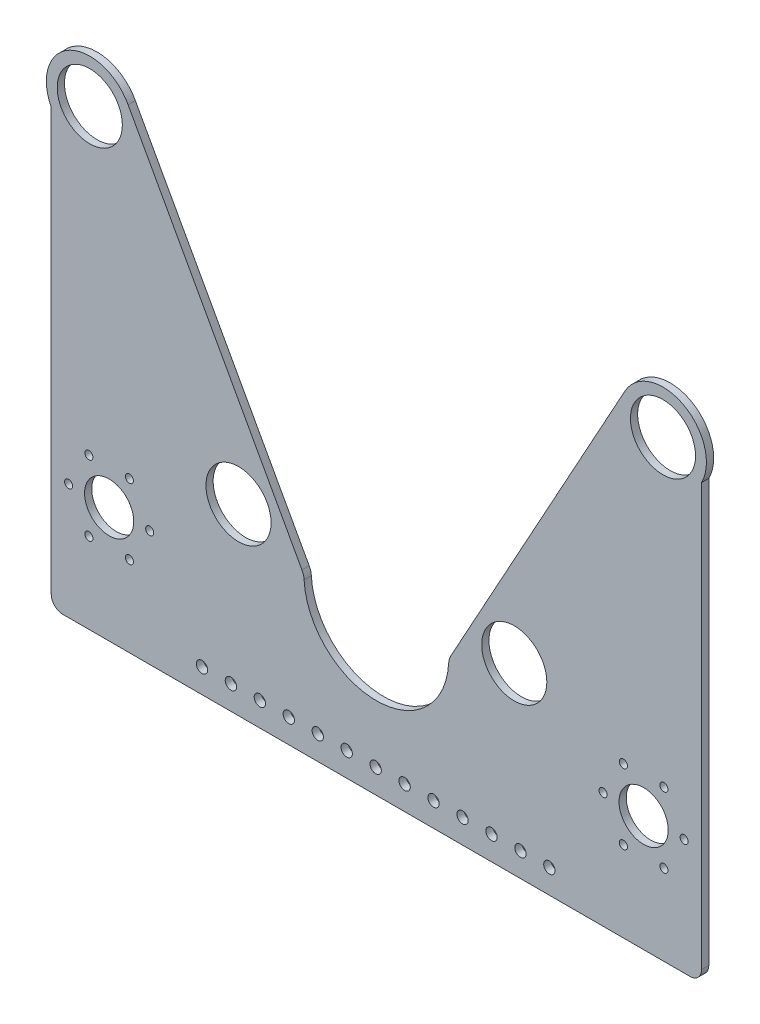
SolidWorks part; units mm, degrees
ref_plane "Front Plane" through (0, 0, 0) normal (0, 0, 1) x (1, 0, 0)
ref_plane "Top Plane" through (0, 0, 0) normal (0, 1, 0) x (1, 0, 0)
ref_plane "Right Plane" through (0, 0, 0) normal (1, 0, 0) x (0, 0, -1)
sketch "Sketch2" plane through (0, 0, 0) normal (0, 0, 1) x (1, 0, 0)
  line L0 (-106.68, -1076.9295) -> (-106.68, 48923.0705) construction
  line L1 (142.6324, 122.4629) -> (142.6324, -29.9371)
  line L2 (106.68, -1098.4025) -> (106.68, 48901.5975) construction
  line L3 (31.75, 0) -> (108.9183, 140.209)
  line L4 (0, -1082.0685) -> (0, 48917.9315) construction
  line L5 (-106.68, -44.45) -> (106.68, -44.45) construction
  line L8 (106.68, -55.9582) -> (106.68, -31.75)
  line L9 (-31.75, 0) -> (-108.9183, 140.209)
  line L10 (31.75, 0) -> (108.9183, 140.209)
  line L22 (-142.6324, -56.7419) -> (-142.6324, -62.6205)
  line L33 (-106.5644, -31.75) -> (0, -31.75) construction
  line L34 (-142.6324, 122.4629) -> (-142.6324, -29.9371)
  line L36 (-261.1394, 46.2048) -> (-243.4617, 46.2048) construction
  line L37 (-243.4617, 46.2048) -> (-243.4617, 28.5272) construction
  line L41 (-238.3305, 62.766) -> (-266.2705, 62.766) construction
  line L42 (-233.2505, 57.686) -> (-233.2505, 17.046) construction
  line L43 (-261.1394, 46.2048) -> (-261.1394, 28.5272) construction
  line L44 (-261.1394, 28.5272) -> (-243.4617, 28.5272) construction
  line L45 (-238.3305, 11.966) -> (-266.2705, 11.966) construction
  line L46 (-271.3505, 57.686) -> (-271.3505, 17.046) construction
  line L47 (-233.2505, 62.766) -> (-271.3505, 11.966) construction
  line L48 (-125.73, 3.175) -> (-125.73, -22.225) construction
  line L49 (-1101.9372, -9.525) -> (48898.0628, -9.525) construction
  line L50 (-233.2505, 11.966) -> (-271.3505, 62.766) construction
  line L51 (-239.6005, 56.416) -> (-239.6005, 18.316) construction
  line L52 (-265.0005, 56.416) -> (-239.6005, 56.416) construction
  line L53 (-125.73, 3.175) -> (-106.68, 3.175) construction
  line L54 (-142.6324, -56.7419) -> (142.6324, -56.7419) construction
  line L55 (-142.6324, -29.9371) -> (-142.6324, -56.7419)
  line L56 (142.6324, -29.9371) -> (142.6324, -56.7419)
  line L57 (-137.5524, -67.7005) -> (137.5524, -67.7005)
  line L58 (142.6324, -62.6205) -> (142.6324, -56.7419)
  arc A0 (-31.75, 0) -> (31.75, 0) centre (0, 0) ccw
  arc A1 (-108.9183, 140.209) -> (-142.6324, 122.4629) centre (-125.7268, 131.2438) ccw
  circle A2 centre (-60.4845, 12.7) radius 14.2875
  arc A3 (31.75, 0) -> (0, 31.75) centre (0, 0) ccw construction
  arc A4 (0, 31.75) -> (-31.75, 0) centre (0, 0) ccw construction
  arc A5 (137.5524, -67.7005) -> (142.6324, -62.6205) centre (137.5524, -62.6205) ccw
  arc A6 (-142.6324, -62.6205) -> (-137.5524, -67.7005) centre (-137.5524, -62.6205) ccw
  circle A7 centre (-125.7268, 131.2438) radius 14.2875
  circle A9 centre (-60.4845, 12.7) radius 19.05 construction
  circle A10 centre (60.4845, 12.7) radius 19.05 construction
  arc A11 (108.9183, 140.209) -> (142.6324, 122.4629) centre (125.7268, 131.2438) cw
  circle A12 centre (125.7268, 131.2438) radius 14.2875
  arc A40 (-142.6324, 122.4629) -> (-108.9183, 140.209) centre (-125.7268, 131.2438) ccw construction
  arc A41 (142.6324, 122.4629) -> (108.9183, 140.209) centre (125.7268, 131.2438) cw construction
  circle A42 centre (60.4845, 12.7) radius 14.2875
  circle A44 centre (-76.5175, -57.15) radius 2.4892
  circle A45 centre (-63.8175, -57.15) radius 2.4892
  circle A46 centre (-51.1175, -57.15) radius 2.4892
  circle A47 centre (-38.4175, -57.15) radius 2.4892
  circle A48 centre (-25.7175, -57.15) radius 2.4892
  circle A49 centre (-13.0175, -57.15) radius 2.4892
  circle A50 centre (-0.3175, -57.15) radius 2.4892
  circle A51 centre (12.3825, -57.15) radius 2.4892
  circle A52 centre (25.0825, -57.15) radius 2.4892
  circle A53 centre (37.7825, -57.15) radius 2.4892
  circle A54 centre (50.4825, -57.15) radius 2.4892
  circle A55 centre (63.1825, -57.15) radius 2.4892
  circle A56 centre (75.8825, -57.15) radius 2.4892
  arc A100 (-260.1552, 27.7564) -> (-262.1235, 29.2979) centre (-261.1394, 28.5272) ccw construction
  arc A101 (-262.1235, 29.2979) -> (-260.1552, 27.7564) centre (-261.1394, 28.5272) ccw construction
  arc A102 (-244.4458, 29.2979) -> (-242.4776, 27.7564) centre (-243.4617, 28.5272) ccw construction
  arc A103 (-242.4776, 27.7564) -> (-244.4458, 29.2979) centre (-243.4617, 28.5272) ccw construction
  arc A104 (-242.4776, 45.4341) -> (-244.4458, 46.9756) centre (-243.4617, 46.2048) ccw construction
  arc A105 (-244.4458, 46.9756) -> (-242.4776, 45.4341) centre (-243.4617, 46.2048) ccw construction
  arc A106 (-262.1235, 46.9756) -> (-260.1552, 45.4341) centre (-261.1394, 46.2048) ccw construction
  arc A107 (-260.1552, 45.4341) -> (-262.1235, 46.9756) centre (-261.1394, 46.2048) ccw construction
  circle A108 centre (-252.3005, 37.366) radius 7.3172 construction
  circle A109 centre (-265.0005, 56.416) radius 3.175 construction
  circle A110 centre (-239.6005, 56.416) radius 3.175 construction
  circle A111 centre (-239.6005, 18.316) radius 3.175 construction
  circle A112 centre (-265.0005, 18.316) radius 3.175 construction
  arc A113 (-266.2705, 11.966) -> (-271.3505, 17.046) centre (-266.2705, 17.046) cw construction
  arc A114 (-233.2505, 17.046) -> (-238.3305, 11.966) centre (-238.3305, 17.046) cw construction
  arc A115 (-238.3305, 62.766) -> (-233.2505, 57.686) centre (-238.3305, 57.686) cw construction
  arc A116 (-266.2705, 62.766) -> (-271.3505, 57.686) centre (-266.2705, 57.686) ccw construction
  circle A128 centre (-117.2324, -16.9005) radius 10.795
  circle A129 centre (117.2324, -16.9005) radius 10.795
  circle A132 centre (-135.0124, -16.9005) radius 1.778
  circle A133 centre (-126.1224, -1.5026) radius 1.778
  circle A134 centre (-108.3424, -1.5026) radius 1.778
  circle A135 centre (-99.4524, -16.9005) radius 1.778
  circle A136 centre (-108.3424, -32.2984) radius 1.778
  circle A137 centre (-126.1224, -32.2984) radius 1.778
  circle A138 centre (99.4524, -16.9005) radius 1.778
  circle A139 centre (108.3424, -1.5026) radius 1.778
  circle A140 centre (126.1224, -1.5026) radius 1.778
  circle A141 centre (135.0124, -16.9005) radius 1.778
  circle A142 centre (126.1224, -32.2984) radius 1.778
  circle A143 centre (108.3424, -32.2984) radius 1.778
  point P82 (-117.2324, -16.9005)
  point P83 (106.68, -30.0086)
  point P97 (-106.68, -29.6005)
  point P98 (117.2324, -16.9005)
  point P154 (-125.73, -9.525)
  dimension "D7" = 131.2438
  dimension "D8" = 25.4
  dimension "D9" = 25.4
  dimension "D3" = 44.45
  dimension "D14" = 106.68
  dimension "D17" = 38.1
  dimension "D5" = 5.08
  dimension "D15" = 31.75
  dimension "D16" = 28.575
  dimension "D18" = 28.575
  dimension "D19" = 19.05
  dimension "D21" = 125.7268
  dimension "D33" = 6.35
  dimension "D35" = 8.8388
  dimension "D37" = 8.8388
  dimension "D42" = 36.068
  dimension "D34" = 6.35
  dimension "D36" = 1.25
  dimension "D38" = 5.08
  dimension "D11" = 50.8
  dimension "D12" = 50.8
  dimension "D1" = 28.828
  dimension "D6" = 10.9586
  dimension "D10" = 35.9524
  dimension "D20" = 142.6324
  dimension "D25" = 152.4
  dimension "D26" = 12.7
  dimension "D32" = 6.35
  dimension "D29" = 17.6777
  dimension "D30" = 50.8
  dimension "D31" = 38.1
  dimension "D39" = 25.4
  dimension "D40" = 38.1
  dimension "D41" = 16.9024
extrude "Boss-Extrude1" add sketch "Sketch2" along normal blind 3.175
sketch "Sketch3" plane through (0, 0, 3.175) normal (0, 0, -1) x (-1, 0, 0)
  line L0 (-125.7268, 150.2938) -> (49874.2732, 150.2938) construction
  line L1 (-144.7768, 131.2438) -> (-144.7768, 50131.2438) construction
  point P4 (-144.7768, 150.2938)
fillet "Fillet2" radius 7.62 2 edges at (31.75, 0, 1.5875) (-31.75, 0, 1.5875)
